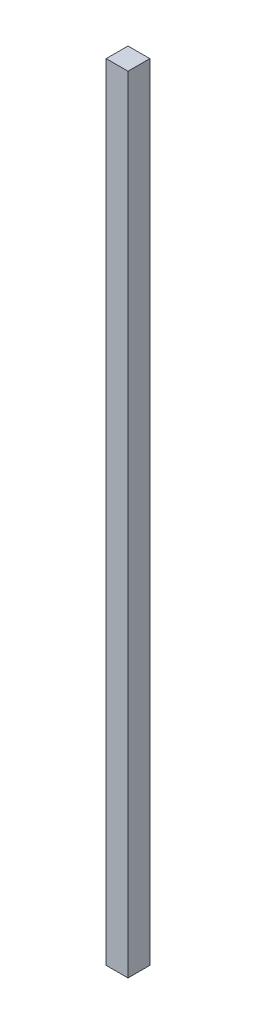
SolidWorks part; units mm, degrees
ref_plane "Front Plane" through (0, 0, 0) normal (0, 0, 1) x (1, 0, 0)
ref_plane "Top Plane" through (0, 0, 0) normal (0, 1, 0) x (1, 0, 0)
ref_plane "Right Plane" through (0, 0, 0) normal (1, 0, 0) x (0, 0, -1)
sketch "Sketch1" plane through (0, 0, 0) normal (0, 1, 0) x (1, 0, 0)
  line L1 (-25.4, -25.4) -> (25.4, -25.4)
  line L2 (-25.4, -25.4) -> (-25.4, 25.4)
  line L3 (-25.4, 25.4) -> (25.4, 25.4)
  line L4 (25.4, -25.4) -> (25.4, 25.4)
  line L5 (-25.4, -25.4) -> (25.4, 25.4) construction
  line L6 (-25.4, 25.4) -> (25.4, -25.4) construction
  point P0 (0, 0)
  dimension "D1" = 50.8
  dimension "D2" = 50.8
extrude "Boss-Extrude1" add sketch "Sketch1" along normal blind 1828.8
